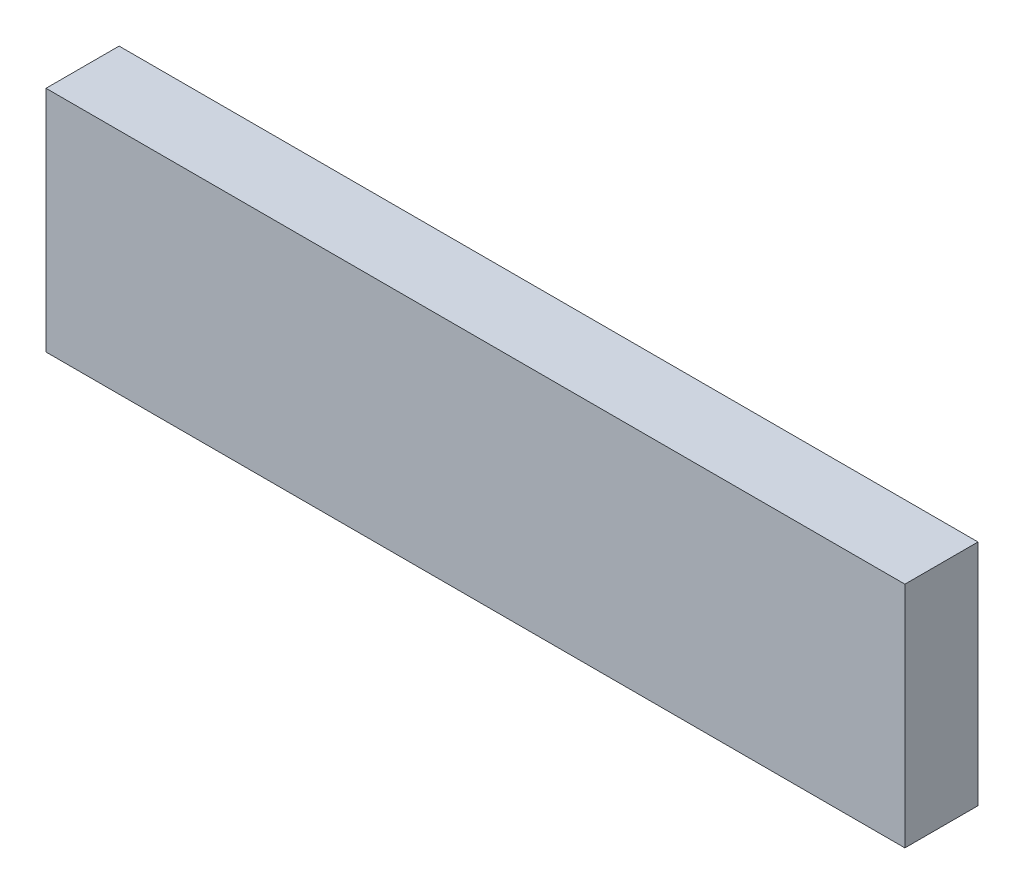
SolidWorks part; units mm, degrees
material "AISI 1020"
ref_plane "Plano frontal" through (0, 0, 0) normal (0, 0, 1) x (1, 0, 0)
ref_plane "Plano superior" through (0, 0, 0) normal (0, 1, 0) x (1, 0, 0)
ref_plane "Plano direito" through (0, 0, 0) normal (1, 0, 0) x (0, 0, -1)
sketch "Esboço1" plane through (0, 0, 0) normal (0, 0, 1) x (1, 0, 0)
  line L1 (47, -5) -> (-47, -5)
  line L2 (47, -5) -> (47, -30)
  line L3 (47, -30) -> (-47, -30)
  line L4 (-47, -5) -> (-47, -30)
  dimension "D1" = 25
extrude "Ressalto-extrusão1" add sketch "Esboço1" along normal blind 8
